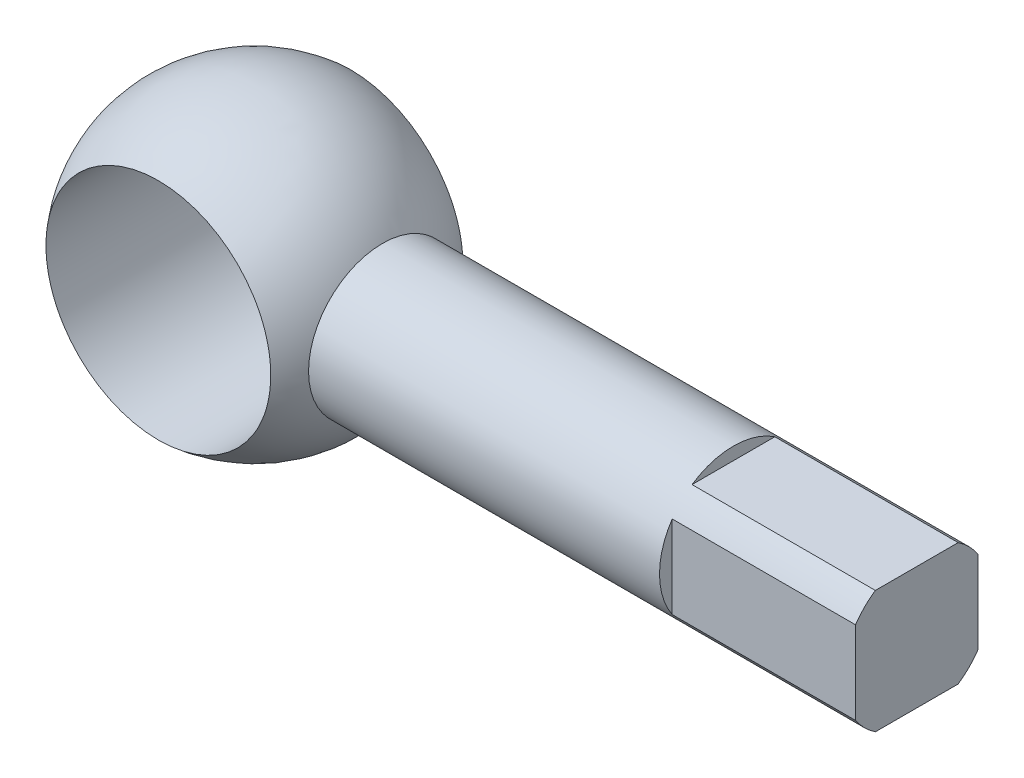
SolidWorks part; units mm, degrees
ref_plane "Front Plane" through (0, 0, 0) normal (0, 0, 1) x (1, 0, 0)
ref_plane "Top Plane" through (0, 0, 0) normal (0, 1, 0) x (1, 0, 0)
ref_plane "Right Plane" through (0, 0, 0) normal (1, 0, 0) x (0, 0, -1)
sketch "Sketch1" plane through (0, 0, 0) normal (0, 0, 1) x (1, 0, 0)
  line L1 (-25, 0) -> (112, 0)
  line L2 (21.6506, 12.5) -> (112, 12.5)
  line L3 (112, 12.5) -> (112, 0)
  arc A0 (-25, 0) -> (21.6506, 12.5) centre (0, 0) cw
  dimension "D1" = 25
  dimension "D2" = 12.5
  dimension "D3" = 112
revolve "Revolve1" add sketch "Sketch1" angle 360 about L1
sketch "Sketch2" plane through (0, 0, 0) normal (0, 0, 1) x (1, 0, 0)
  circle A2 centre (0, 0) radius 19
  point P1 (3.0421, 3.7272)
  dimension "D1" = 38
extrude "Cut-Extrude1" cut sketch "Sketch2" against normal through all both and the other way through all
sketch "Sketch4" plane through (112, 0, 0) normal (1, 0, 0) x (0, 0, -1)
  line L0 (-7, 10.3562) -> (7, 10.3562)
  circle A0 centre (0, 0) radius 12.5 construction
  arc A1 (7, 10.3562) -> (-7, 10.3562) centre (0, 0) ccw
  dimension "D1" = 14
extrude "Cut-Extrude3" cut sketch "Sketch4" against normal blind 31 and the other way through all
pattern_circular "CirPattern1" count 4 over 360 about axis through (0, 0, 0) along (1, 0, 0) of "Cut-Extrude3"
